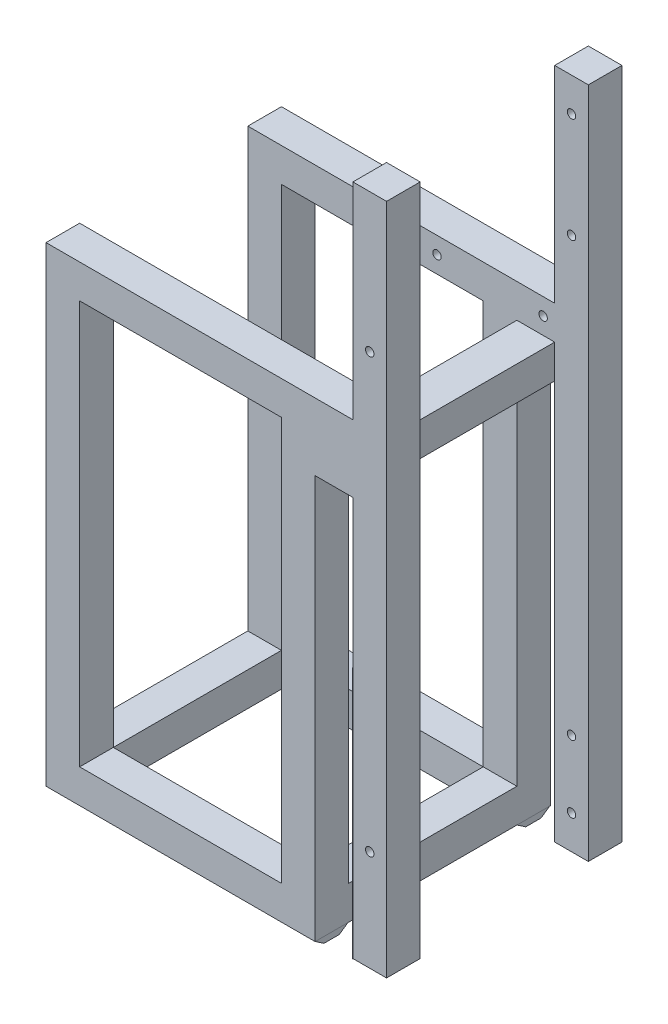
SolidWorks part; units mm, degrees
material "1060 Alloy"
ref_plane "Front Plane" through (0, 0, 0) normal (0, 0, 1) x (1, 0, 0)
ref_plane "Top Plane" through (0, 0, 0) normal (0, 1, 0) x (1, 0, 0)
ref_plane "Right Plane" through (0, 0, 0) normal (1, 0, 0) x (0, 0, -1)
sketch "Sketch1" plane through (0, 0, 0) normal (0, 0, 1) x (1, 0, 0)
  line L1 (-73.5034, -168.3944) -> (129.6966, -168.3944)
  line L2 (129.6966, -168.3944) -> (129.6966, 136.4056)
  line L3 (129.6966, 136.4056) -> (158.2716, 136.4056)
  line L4 (158.2716, 136.4056) -> (158.2716, -165.2194)
  line L5 (158.2716, -165.2194) -> (183.6716, -165.2194)
  line L6 (183.6716, -165.2194) -> (183.6716, 342.7806)
  line L7 (183.6716, 342.7806) -> (158.2716, 342.7806)
  line L8 (158.2716, 342.7806) -> (158.2716, 187.2056)
  line L9 (158.2716, 187.2056) -> (-73.5034, 187.2056)
  line L11 (-73.5034, 187.2056) -> (-73.5034, -168.3944)
  line L13 (-48.1034, -142.9944) -> (104.2966, -142.9944)
  line L14 (-48.1034, -142.9944) -> (-48.1034, 161.8056)
  line L15 (-48.1034, 161.8056) -> (104.2966, 161.8056)
  line L16 (104.2966, -142.9944) -> (104.2966, 161.8056)
  dimension "D1" = 355.6
  dimension "D2" = 203.2
  dimension "D3" = 28.575
  dimension "D4" = 25.4
  dimension "D5" = 508
  dimension "D6" = 155.575
  dimension "D7" = 25.4
  dimension "D8" = 25.4
  dimension "D9" = 25.4
  dimension "D10" = 25.4
  dimension "D11" = 50.8
extrude "Boss-Extrude1" add sketch "Sketch1" along normal blind 177.8
sketch "Sketch2" plane through (0, 187.2056, 0) normal (0, 1, 0) x (1, 0, 0)
  line L0 (-73.5034, -177.8) -> (-73.5034, 0) construction
  line L1 (-73.5034, -25.4) -> (158.2716, -25.4)
  line L2 (-73.5034, -25.4) -> (-73.5034, -152.4)
  line L3 (-73.5034, -152.4) -> (158.2716, -152.4)
  line L4 (158.2716, -25.4) -> (158.2716, -152.4)
  line L5 (158.2716, -177.8) -> (158.2716, 0) construction
  line L6 (158.2716, 0) -> (-73.5034, 0) construction
  line L7 (158.2716, -177.8) -> (-73.5034, -177.8) construction
  dimension "D1" = 25.4
  dimension "D2" = 25.4
extrude "Cut-Extrude1" cut sketch "Sketch2" against normal blind 25.4
sketch "Sketch3" plane through (-73.5034, 0, 0) normal (-1, 0, 0) x (0, 0, 1)
  line L0 (177.8, -168.3944) -> (0, -168.3944) construction
  line L1 (25.4, 161.8056) -> (152.4, 161.8056)
  line L2 (25.4, 161.8056) -> (25.4, -142.9944)
  line L3 (25.4, -142.9944) -> (152.4, -142.9944)
  line L4 (152.4, 161.8056) -> (152.4, -142.9944)
  dimension "D1" = 25.4
extrude "Cut-Extrude2" cut sketch "Sketch3" against normal blind 25.4
sketch "Sketch4" plane through (104.2966, 0, 0) normal (-1, 0, 0) x (0, 0, 1)
  line L0 (177.8, -142.9944) -> (0, -142.9944) construction
  line L1 (25.4, 161.8056) -> (152.4, 161.8056)
  line L2 (25.4, 161.8056) -> (25.4, -142.9944)
  line L3 (25.4, -142.9944) -> (152.4, -142.9944)
  line L4 (152.4, 161.8056) -> (152.4, -142.9944)
  line L5 (177.8, -142.9944) -> (177.8, 161.8056) construction
  dimension "D1" = 25.4
extrude "Cut-Extrude3" cut sketch "Sketch4" against normal blind 25.4
sketch "Sketch5" plane through (0, -142.9944, 0) normal (0, 1, 0) x (1, 0, 0)
  line L1 (104.2966, -25.4) -> (-48.1034, -25.4)
  line L2 (104.2966, -25.4) -> (104.2966, -152.4)
  line L3 (104.2966, -152.4) -> (-48.1034, -152.4)
  line L4 (-48.1034, -25.4) -> (-48.1034, -152.4)
extrude "Cut-Extrude4" cut sketch "Sketch5" against normal blind 25.4
sketch "Sketch6" plane through (183.6716, 0, 0) normal (1, 0, 0) x (0, 0, -1)
  line L0 (-177.8, 342.7806) -> (0, 342.7806) construction
  line L1 (-152.4, 342.7806) -> (-25.4, 342.7806)
  line L2 (-152.4, 342.7806) -> (-152.4, -165.2194)
  line L3 (-152.4, -165.2194) -> (-25.4, -165.2194)
  line L4 (-25.4, 342.7806) -> (-25.4, -165.2194)
  line L5 (-177.8, -165.2194) -> (0, -165.2194) construction
  line L6 (-177.8, -165.2194) -> (-177.8, 342.7806) construction
  line L7 (0, -165.2194) -> (0, 342.7806) construction
  dimension "D1" = 25.4
  dimension "D2" = 25.4
extrude "Cut-Extrude5" cut sketch "Sketch6" against normal blind 25.4
sketch "Sketch7" plane through (0, 0, 177.8) normal (0, 0, 1) x (1, 0, 0)
  line L0 (170.9716, 342.7806) -> (170.9716, -165.2194) construction
  line L1 (183.6716, 342.7806) -> (158.2716, 342.7806) construction
  line L2 (158.2716, -165.2194) -> (183.6716, -165.2194) construction
  circle A0 centre (170.9716, 238.0056) radius 3.175
  circle A1 centre (170.9716, -89.0194) radius 3.175
  dimension "D1" = 6.35
  dimension "D3" = 6.35
  dimension "D2" = 104.775
  dimension "D4" = 76.2
extrude "Cut-Extrude6" cut sketch "Sketch7" against normal up to surface (177.8 mm away) up to face at (111.2816, 66.5556, 0)
sketch "Sketch8" plane through (0, 0, 152.4) normal (0, 0, -1) x (-1, 0, 0)
  line L0 (-158.2716, 187.2056) -> (-158.2716, 161.8056) construction
  line L1 (-158.2716, 161.8056) -> (-158.2716, 174.5056) construction
  line L2 (-158.2716, 174.5056) -> (73.5034, 174.5056) construction
  line L3 (73.5034, -142.9944) -> (73.5034, 187.2056) construction
  line L4 (-170.9716, 342.7806) -> (-170.9716, -165.2194) construction
  line L5 (-158.2716, 342.7806) -> (-183.6716, 342.7806) construction
  line L6 (-158.2716, -165.2194) -> (-183.6716, -165.2194) construction
  line L7 (-158.2716, 342.7806) -> (-158.2716, 187.2056) construction
  circle A0 centre (-69.3716, 174.5056) radius 3.175
  circle A1 centre (-170.9716, 317.3806) radius 3.175
  circle A2 centre (-170.9716, -139.8194) radius 3.175
  circle A3 centre (-149.5403, 174.5056) radius 3.175
  point P20 (0, 0)
  dimension "D1" = 6.35
  dimension "D3" = 6.35
  dimension "D5" = 6.35
  dimension "D7" = 6.35
  dimension "D2" = 142.875
  dimension "D4" = 25.4
  dimension "D6" = 25.4
  dimension "D8" = 8.7312
extrude "Cut-Extrude7" cut sketch "Sketch8" against normal blind 12.7 and the other way blind 139.7
sketch "Sketch10" plane through (-73.5034, 0, 0) normal (-1, 0, 0) x (0, 0, 1)
  line L2 (177.8, -168.3944) -> (152.4, -168.3944)
  line L5 (170.8726, -173.1569) -> (159.3274, -173.1569) construction
  line L9 (170.8726, -173.1569) -> (159.3274, -173.1569) construction
  line L11 (159.3274, -173.1569) -> (152.4, -168.3944)
  line L12 (177.8, -168.3944) -> (170.8726, -173.1569)
  line L13 (152.4, -168.3944) -> (159.3274, -173.1569) construction
  line L14 (170.8726, -173.1569) -> (159.3274, -173.1569) construction
  line L15 (170.8726, -173.1569) -> (177.8, -168.3944) construction
  line L16 (170.8726, -173.1569) -> (159.3274, -173.1569)
  point P10 (165.1, -168.3944)
extrude "Boss-Extrude2" add sketch "Sketch10" against normal blind 202.692 from offset 0.254 offset against normal yes
ref_plane "Plane1" through (0, 0, 88.9) normal (0, 0, 1) x (1, 0, 0)
mirror "Mirror1" about plane through (0, 0, 88.9) normal (0, 0, 1) of "Boss-Extrude2"
sketch "Sketch11" plane through (0, -165.2194, 0) normal (0, -1, 0) x (1, 0, 0)
  line L0 (158.2716, 152.4) -> (158.1171, 177.7995)
  line L1 (153.3968, 170.8433) -> (158.1171, 177.7995)
  line L2 (158.2716, 152.4) -> (153.467, 159.2983)
  line L3 (153.467, 159.2983) -> (153.3968, 170.8433)
  line L4 (158.2716, 152.4) -> (158.2716, 177.8) construction
  line L5 (183.6716, 165.1) -> (158.2716, 165.1) construction
  line L6 (183.6716, 177.8) -> (183.6716, 152.4) construction
  line L7 (158.2716, 0) -> (158.1171, 25.3995)
  line L8 (153.3968, 18.4433) -> (158.1171, 25.3995)
  line L9 (158.2716, 0) -> (153.467, 6.8983)
  line L10 (153.467, 6.8983) -> (153.3968, 18.4433)
  point P12 (0, 0)
  point P13 (158.2258, 152.4)
  point P17 (158.2716, 0)
  dimension "D1" = 4.7625
  dimension "D2" = 8.4066
  dimension "D3" = 8.4066
  dimension "D4" = 11.5452
  dimension "D5" = 4.7625
  dimension "D6" = 11.545
  dimension "D7" = 25.3995
  dimension "D8" = 8.4066
  dimension "D9" = 8.4066
extrude "Boss-Extrude3" add sketch "Sketch11" against normal blind 190.5 from offset 0.254 separate body
